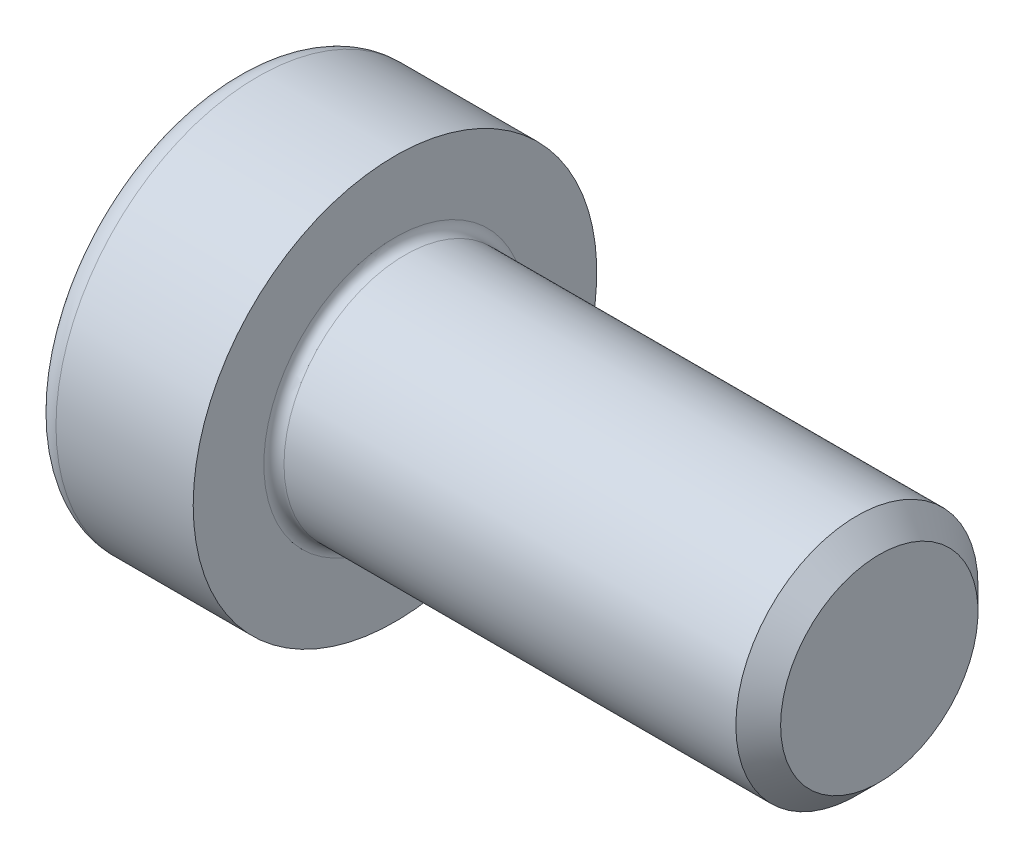
SolidWorks part; units mm, degrees
revolve "Base-Revolve" add sketch "BodySke"
sketch "BodySke" plane through (0, 0, 0) normal (0, 0, 1) x (1, 0, 0)
  line L0 (0, 0) -> (0, 5)
  line L1 (0, 5) -> (4, 5)
  line L2 (4, 5) -> (4, 3)
  line L3 (4, 3) -> (15.4455, 3)
  line L4 (16, 2.4455) -> (16, 0)
  line L5 (16, 0) -> (0, 0)
  line L6 (-31.75, 0) -> (127, 0) construction
  line L8 (16, 2.4455) -> (15.4455, 3)
  line L10 (16, -2.4455) -> (15.4455, -3) construction
  line L11 (5, 4.525) -> (5, -1.825) construction
  line L12 (4, 4.525) -> (4, -1.825) construction
  line L13 (-44, 4.525) -> (-44, -1.825) construction
  dimension "Head_ht" = 4
  dimension "Length" = 12
  dimension "Body_ch_ang" = 45
  dimension "Diameter" = 6
  dimension "Minor_dia" = 4.891
  dimension "Advance" = 1
  dimension "Thread_nom" = 12
  dimension "Thread_length" = 60
  dimension "Head_dia" = 10
cosmetic thread "ThreadCosmetic"
fillet "Fillet1" radius 0.25 1 edges at (4, 0, 3)
fillet "Fillet2" radius 0.6 1 edges at (0, 0, 5)
ref_plane "Plane1" through (0, 0, 0) normal (0, 0, 1) x (1, 0, 0)
ref_plane "Plane2" through (0, 0, 0) normal (0, 1, 0) x (1, 0, 0)
ref_plane "Plane3" through (0, 0, 0) normal (1, 0, 0) x (0, 0, -1)
other "Configuration Table"
sketch "Sketch2" plane through (0, 0, 0) normal (0, 0, 1) x (1, 0, 0)
  line L0 (0, 2) -> (3, 2)
  line L1 (3, 2) -> (4.1547, 0)
  line L2 (-31.75, 0) -> (127, 0) construction
  line L3 (4.1547, 0) -> (0, 0)
  line L4 (0, 0) -> (0, 2)
  line L6 (0, 0) -> (47.625, 0) construction
  dimension "D1" = 2
  dimension "D2" = 60
  dimension "Depth" = 3
revolve "Hex-PreBroach" cut sketch "Sketch2" angle 360 about L6
sketch "Sketch3" plane through (0, 0, 0) normal (-1, 0, 0) x (0, 0.5, 0.866)
  line L0 (1.1547, 2) -> (-1.1547, 2)
  line L1 (-1.1547, 2) -> (-2.3094, 0)
  line L2 (1.1547, 2) -> (2.3094, 0)
  line L3 (1.1547, -2) -> (2.3094, 0)
  line L4 (1.1547, -2) -> (-1.1547, -2)
  line L5 (-1.1547, -2) -> (-2.3094, 0)
  dimension "D1" = 2
  dimension "D2" = 2
  dimension "Hex_size" = 4
extrude "Hex" cut sketch "Sketch3" against normal blind 3
sketch "ThdSchSke" plane through (0, 0, 0) normal (0, 0, 1) x (1, 0, 0)
  line L0 (7, -2.4455) -> (6.6117, -3)
  line L1 (7, -2.4455) -> (7.3883, -3)
  line L2 (7.3883, -3) -> (7.3883, -3.75)
  line L3 (-3.175, 0) -> (5.1513, 0) construction
  line L4 (0, 4.4) -> (0, -4.4) construction
  line L5 (7.3883, -3.75) -> (6.6117, -3.75)
  line L6 (6.6117, -3.75) -> (6.6117, -3)
  dimension "Thread_minor" = 4.891
  dimension "Diameter" = 6
  dimension "Start" = 7
revolve "ThreadSchematic" [suppressed] cut sketch "ThdSchSke" angle 360 about L3
pattern_linear "ThdSchPat" [suppressed]
equation "\"D2@Sketch3\" = \"Hex_size@Sketch3\" / 2"
equation "\"D1@Sketch3\" = \"Hex_size@Sketch3\" / 2"
equation "\"D1@Sketch2\" = \"Hex_size@Sketch3\" / 2"
equation "\"Thread_minor@ThreadCosmetic\"  =  \"Minor_dia@BodySke\""
equation "\"Depth@Sketch2\" =  \"Key_eng@Hex\""
equation "\"Thread_length@ThreadCosmetic\" = ((sgn( (\"Length@BodySke\" - \"Advance@BodySke\" * 3.0) - \"Thread_nom@BodySke\" )-1)*( (\"Length@BodySke\" - \"Advance@BodySke\" * 3.0) - \"Thread_nom@BodySke\" ))/-2+ \"Thread_nom@BodySke\""
equation "\"Thread_minor@ThdSchSke\" = \"Minor_dia@BodySke\""
equation "\"Diameter@ThdSchSke\" = \"Diameter@BodySke\""
equation "\"Overcut@ThdSchSke\" = \"Diameter@BodySke\" * 1.25"
equation "\"Start@ThdSchSke\" = \"Head_ht@BodySke\" + \"Length@BodySke\" - \"Thread_length@ThreadCosmetic\"  '---Non-countersunk---"
equation "\"Num_threads@ThdSchPat\" = int( \"Thread_length@ThreadCosmetic\" / \"Advance@BodySke\" + 0.999 )  + 1"
equation "\"Advance@ThdSchPat\" = \"Thread_length@ThreadCosmetic\" /  (\"Num_threads@ThdSchPat\" - 1) 'relax it"
equation "\"Num_threads@ThdSchPat\" = \"Num_threads@ThdSchPat\" - sgn( \"Num_threads@ThdSchPat\" - 1) '---chamfered tips only---"
